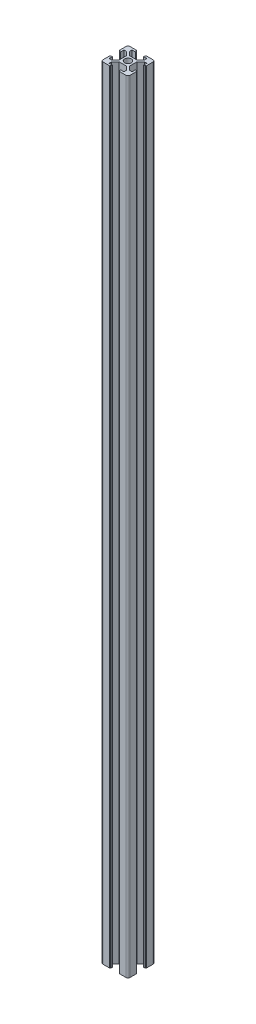
SolidWorks part; units mm, degrees
ref_plane "前视基准面" through (0, 0, 0) normal (0, 0, 1) x (1, 0, 0)
ref_plane "上视基准面" through (0, 0, 0) normal (0, 1, 0) x (1, 0, 0)
ref_plane "右视基准面" through (0, 0, 0) normal (1, 0, 0) x (0, 0, -1)
other "Configuration Table"
sketch "草图2" plane through (0, 0, 0) normal (0, 1, 0) x (1, 0, 0)
  line L0 (-3.6, 10) -> (-3.6, 9.5)
  line L1 (-3.6, 9.5) -> (-3.1, 9.5)
  line L2 (-3.1, 9.5) -> (-3.1, 8.5)
  line L3 (-3.1, 8.5) -> (-5.5, 8.5)
  line L4 (-8.5, -10) -> (-3.6, -10)
  line L5 (-10, -8.5) -> (-10, -3.6)
  line L6 (8.5, 10) -> (3.6, 10)
  line L7 (10, 8.5) -> (10, 3.6)
  line L8 (0, 14.8756) -> (0, 0) construction
  line L9 (0, 0) -> (14.1675, 0) construction
  line L10 (-5.5, 8.5) -> (-5.5, 6.65)
  line L11 (-5.5, 6.65) -> (-2.75, 3.9)
  line L12 (-2.75, 3.9) -> (2.75, 3.9)
  line L13 (5.5, 6.65) -> (2.75, 3.9)
  line L14 (5.5, 8.5) -> (5.5, 6.65)
  line L15 (3.1, 8.5) -> (5.5, 8.5)
  line L16 (3.1, 9.5) -> (3.1, 8.5)
  line L17 (3.6, 9.5) -> (3.1, 9.5)
  line L18 (3.6, 10) -> (3.6, 9.5)
  line L19 (-3.6, 10) -> (-8.5, 10)
  line L20 (10, 3.6) -> (9.5, 3.6)
  line L21 (9.5, 3.6) -> (9.5, 3.1)
  line L22 (9.5, 3.1) -> (8.5, 3.1)
  line L23 (8.5, 3.1) -> (8.5, 5.5)
  line L24 (8.5, 5.5) -> (6.65, 5.5)
  line L25 (6.65, 5.5) -> (3.9, 2.75)
  line L26 (3.9, 2.75) -> (3.9, -2.75)
  line L27 (6.65, -5.5) -> (3.9, -2.75)
  line L28 (8.5, -5.5) -> (6.65, -5.5)
  line L29 (8.5, -3.1) -> (8.5, -5.5)
  line L30 (9.5, -3.1) -> (8.5, -3.1)
  line L31 (9.5, -3.6) -> (9.5, -3.1)
  line L32 (10, -3.6) -> (9.5, -3.6)
  line L33 (3.6, -10) -> (3.6, -9.5)
  line L34 (3.6, -9.5) -> (3.1, -9.5)
  line L35 (3.1, -9.5) -> (3.1, -8.5)
  line L36 (3.1, -8.5) -> (5.5, -8.5)
  line L37 (5.5, -8.5) -> (5.5, -6.65)
  line L38 (5.5, -6.65) -> (2.75, -3.9)
  line L39 (2.75, -3.9) -> (-2.75, -3.9)
  line L40 (-5.5, -6.65) -> (-2.75, -3.9)
  line L41 (-5.5, -8.5) -> (-5.5, -6.65)
  line L42 (-3.1, -8.5) -> (-5.5, -8.5)
  line L43 (-3.1, -9.5) -> (-3.1, -8.5)
  line L44 (-3.6, -9.5) -> (-3.1, -9.5)
  line L45 (-3.6, -10) -> (-3.6, -9.5)
  line L46 (-10, -3.6) -> (-9.5, -3.6)
  line L47 (-9.5, -3.6) -> (-9.5, -3.1)
  line L48 (-9.5, -3.1) -> (-8.5, -3.1)
  line L49 (-8.5, -3.1) -> (-8.5, -5.5)
  line L50 (-8.5, -5.5) -> (-6.65, -5.5)
  line L51 (-6.65, -5.5) -> (-3.9, -2.75)
  line L52 (-3.9, -2.75) -> (-3.9, 2.75)
  line L53 (-6.65, 5.5) -> (-3.9, 2.75)
  line L54 (-8.5, 5.5) -> (-6.65, 5.5)
  line L55 (-8.5, 3.1) -> (-8.5, 5.5)
  line L56 (-9.5, 3.1) -> (-8.5, 3.1)
  line L57 (-9.5, 3.6) -> (-9.5, 3.1)
  line L58 (-10, 3.6) -> (-9.5, 3.6)
  line L59 (3.6, -10) -> (8.5, -10)
  line L60 (-10, 3.6) -> (-10, 8.5)
  line L61 (10, -3.6) -> (10, -8.5)
  circle A0 centre (0, 0) radius 2.5
  arc A1 (-10, 8.5) -> (-8.5, 10) centre (-8.5, 8.5) cw
  arc A2 (10, 8.5) -> (8.5, 10) centre (8.5, 8.5) ccw
  arc A3 (-8.5, -10) -> (-10, -8.5) centre (-8.5, -8.5) cw
  arc A4 (8.5, -10) -> (10, -8.5) centre (8.5, -8.5) ccw
  point P0 (-10, 0)
  point P1 (10, 0)
  point P2 (0, 10)
  point P3 (0, -10)
  point P4 (0, 0)
  point P5 (-10, -10)
  point P6 (10, -10)
  point P7 (10, 10)
  point P8 (-10, 10)
  point P36 (-10, 10)
  point P39 (10, 10)
  dimension "D1" = 11
  dimension "D2" = 20
  dimension "D3" = 6.2
  dimension "D4" = 7.2
  dimension "D5" = 6.1
  dimension "D6" = 5
  dimension "D7" = 1.5
  dimension "D8" = 45
  dimension "D9" = 0.5
  dimension "D10" = 1
  dimension "D11" = 5.5
extrude "凸台-拉伸1" add sketch "草图2" along normal blind 580
